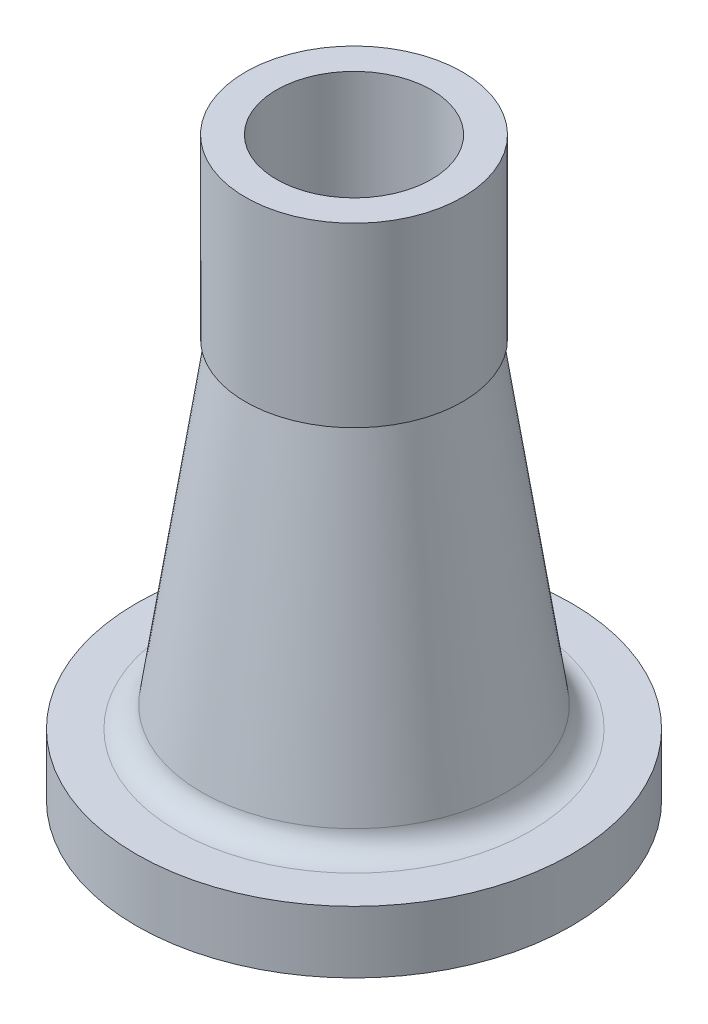
SolidWorks part; units mm, degrees
ref_plane "Front Plane" through (0, 0, 0) normal (0, 0, 1) x (1, 0, 0)
ref_plane "Top Plane" through (0, 0, 0) normal (0, 1, 0) x (1, 0, 0)
ref_plane "Right Plane" through (0, 0, 0) normal (1, 0, 0) x (0, 0, -1)
sketch "Sketch3" plane through (0, 0, 0) normal (0, 0, 1) x (1, 0, 0)
  line L1 (25, 185.8995) -> (35, 185.8995)
  line L2 (35, 185.8995) -> (35, 128.7876)
  line L3 (35, 128.7876) -> (33.9638, 128.7876)
  line L4 (42.4066, 3.8995) -> (50, 3.8995)
  line L5 (50, 3.8995) -> (50, 0)
  line L6 (50, 0) -> (70.1245, 0)
  line L7 (70.1245, 0) -> (70.1245, 20)
  line L8 (70.1245, 20) -> (50.1245, 20)
  line L9 (50.1245, 20) -> (33.9638, 128.7876)
  line L10 (25, 185.8995) -> (25, 121.0734)
  line L11 (42.4066, 3.8995) -> (25, 121.0734)
  line L12 (25, 185.8995) -> (25, 128.7876) construction
  line L13 (40.2331, 18.5306) -> (24.0723, 127.3182) construction
  line L14 (0, 0) -> (0, 237.913) construction
  point P17 (46.2033, 3.8995)
  dimension "D1" = 25
  dimension "D2" = 33.9638
  dimension "D3" = 35
  dimension "D4" = 42.4066
  dimension "D5" = 46.2033
  dimension "D6" = 3.8995
  dimension "D9" = 121.0734
  dimension "D10" = 185.8995
  dimension "D8" = 70.1245
  dimension "D7" = 50.1245
revolve "Revolve1" add sketch "Sketch3" angle 360 about L14
fillet "Fillet1" radius 8 1 edges at (0, 20, -50.1245)
